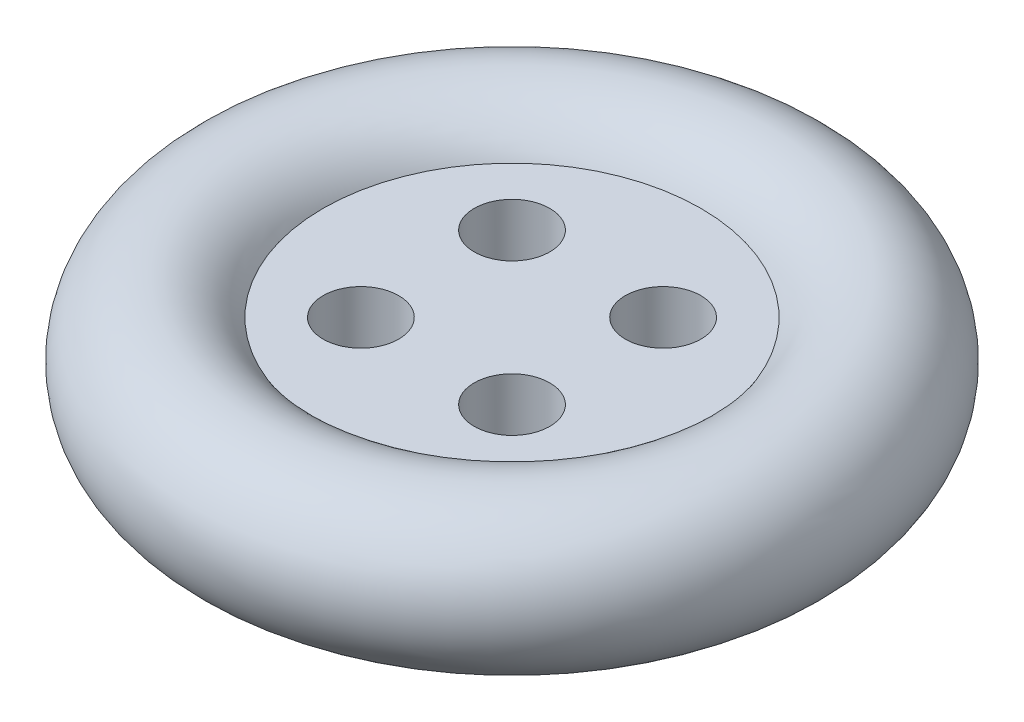
SolidWorks part; units mm, degrees
ref_plane "Front Plane" through (0, 0, 0) normal (0, 0, 1) x (1, 0, 0)
ref_plane "Top Plane" through (0, 0, 0) normal (0, 1, 0) x (1, 0, 0)
ref_plane "Right Plane" through (0, 0, 0) normal (1, 0, 0) x (0, 0, -1)
sketch "Sketch2" plane through (0, 0, 0) normal (1, 0, 0) x (0, 0, -1)
  line L1 (-10, 4) -> (10, 4)
  line L2 (-10, 4) -> (-10, -4)
  line L3 (-10, -4) -> (10, -4)
  line L5 (-10, 4) -> (10, -4) construction
  line L6 (-10, -4) -> (10, 4) construction
  arc A0 (10, -4) -> (10, 4) centre (16.9282, 0) ccw
  point P0 (0, 0)
  dimension "D3" = 16
  dimension "D1" = 20
  dimension "D2" = 8
revolve "Revolve1" add sketch "Sketch2" angle 360 about L2
sketch "Sketch3" plane through (0, 4, 0) normal (0, 1, 0) x (1, 0, 0)
  line L0 (-20, -10) -> (20, -10) construction
  line L1 (0, 10) -> (0, -30) construction
  circle A0 centre (0, -10) radius 20 construction
  circle A1 centre (-8, -2) radius 4
  circle A2 centre (8, -2) radius 4
  circle A3 centre (8, -18) radius 4
  circle A4 centre (-8, -18) radius 4
  point P18 (0, -10)
  dimension "D1" = 8
  dimension "D2" = 8
  dimension "D3" = 8
  dimension "D4" = 4
extrude "Cut-Extrude1" cut sketch "Sketch3" along normal through all both and the other way through all
